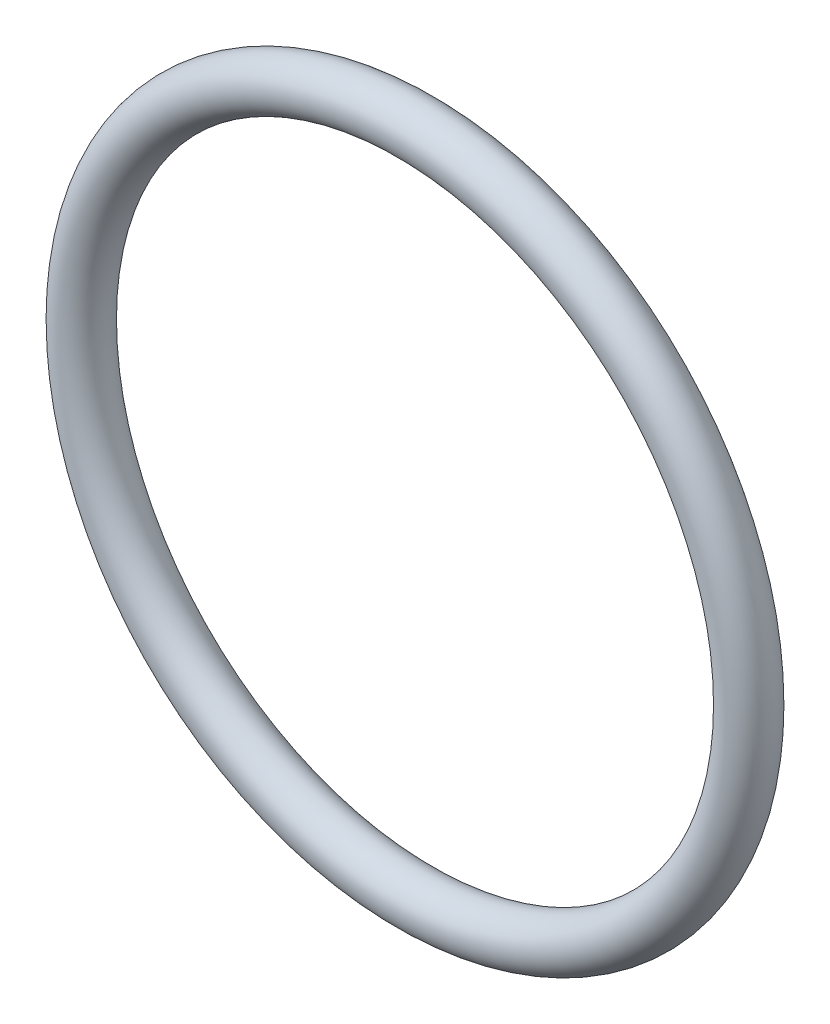
SolidWorks part; units mm, degrees
material "Silicon Rubber"
ref_plane "Front Plane" through (0, 0, 0) normal (0, 0, 1) x (1, 0, 0)
ref_plane "Top Plane" through (0, 0, 0) normal (0, 1, 0) x (1, 0, 0)
ref_plane "Right Plane" through (0, 0, 0) normal (1, 0, 0) x (0, 0, -1)
sketch "Sketch1" plane through (0, 0, 0) normal (0, 1, 0) x (1, 0, 0)
  line L0 (0, 37.5217) -> (0, -29.3552) construction
  line L1 (0, 0) -> (15.748, 0) construction
  line L2 (15.748, 0) -> (17.018, 0) construction
  circle A0 centre (17.018, 0) radius 1.27
  dimension "D1" = 15.748
  dimension "D2" = 1.27
revolve "Revolve1" add sketch "Sketch1" angle 360 about L0
